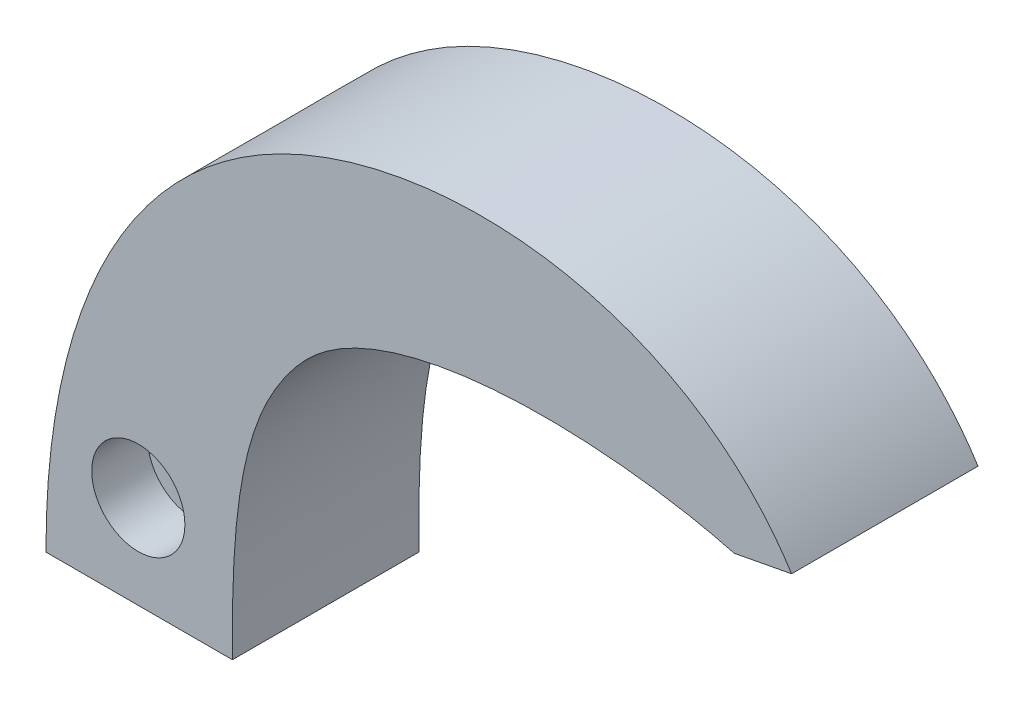
SolidWorks part; units mm, degrees
ref_plane "Plan de face" through (0, 0, 0) normal (0, 0, 1) x (1, 0, 0)
ref_plane "Plan de dessus" through (0, 0, 0) normal (0, 1, 0) x (1, 0, 0)
ref_plane "Plan de droite" through (0, 0, 0) normal (1, 0, 0) x (0, 0, -1)
sketch "Esquisse1" plane through (0, 0, 0) normal (0, 0, 1) x (1, 0, 0)
  line L0 (0, 0) -> (10, 0)
  line L1 (0, 0) -> (40, 0)
  line L2 (0, 0) -> (0, 40)
  line L3 (0, 40) -> (40, 40)
  line L4 (40, 0) -> (40, 40)
  line L5 (40, 17.3515) -> (40, 18.9938)
  spline S0 degree 3 poles (0, 0) (-0.0392, 11.1805) (8.6992, 30.122) (34.0573, 28.3373) (40, 18.9938) knots 0 0 0 0 0.468372 1 1 1 1
  spline S1 degree 3 poles (10, 0) (9.9215, 7.1485) (10.7139, 12.3333) (18.7587, 21.376) (34.363, 19.8984) (40, 17.3515) knots 0 0 0 0 0.337629 0.409351 1 1 1 1
  dimension "D1" = 40
  dimension "D2" = 40
  dimension "D3" = 10
extrude "Boss.-Extru.1" add sketch "Esquisse1" along normal blind 10 contours L0 S1 L5 S0
sketch "Esquisse2" plane through (0, 0, 10) normal (0, 0, 1) x (1, 0, 0)
  line L0 (0, 0) -> (10, 0) construction
  circle A0 centre (4.9519, 5) radius 1.5
  dimension "D1" = 3
  dimension "D2" = 5
extrude "Enlèv. mat.-Extru.1" cut sketch "Esquisse2" against normal blind 10
sketch "Esquisse3" plane through (0, 0, 10) normal (0, 0, 1) x (1, 0, 0)
  circle A0 centre (4.9519, 5) radius 2.5
  dimension "D1" = 5
extrude "Enlèv. mat.-Extru.2" cut sketch "Esquisse3" against normal blind 3
sketch "Esquisse4" plane through (0, 0, 0) normal (0, 0, -1) x (-1, 0, 0)
  circle A0 centre (-4.9519, 5) radius 2.5
  dimension "D1" = 5
extrude "Enlèv. mat.-Extru.3" cut sketch "Esquisse4" against normal blind 3
sketch "Esquisse5" plane through (0, 0, 10) normal (0, 0, 1) x (1, 0, 0)
  line L0 (40, 18.9938) -> (36.9254, 18.408)
  spline S0 degree 3 poles (10, 0) (9.9215, 7.1485) (10.7139, 12.3333) (18.7587, 21.376) (34.363, 19.8984) (40, 17.3515) knots 0 0 0 0 0.337629 0.409351 1 1 1 1 construction
  point P5 (0, 0)
  point P6 (36.9254, 18.408)
  point P7 (0, 0)
extrude "Enlèv. mat.-Extru.5" cut sketch "Esquisse5" against normal blind 10 and the other way through all
